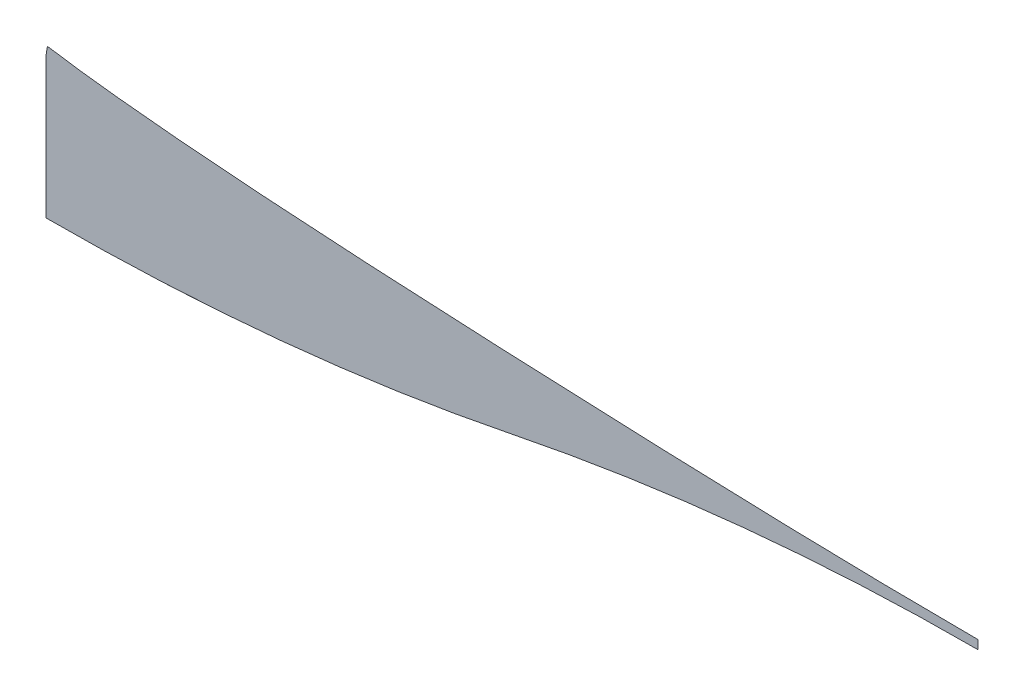
SolidWorks part; units mm, degrees
ref_plane "Front Plane" through (0, 0, 0) normal (0, 0, 1) x (1, 0, 0)
ref_plane "Top Plane" through (0, 0, 0) normal (0, 1, 0) x (1, 0, 0)
ref_plane "Right Plane" through (0, 0, 0) normal (1, 0, 0) x (0, 0, -1)
sketch "Sketch1" plane through (0, 0, 0) normal (0, 0, 1) x (1, 0, 0)
  line L0 (-2512.0431, -12.6587) -> (-2512.0431, -412.6587)
  line L1 (-2512.0431, -412.6587) -> (-3597.8043, -412.6587)
  line L2 (-2508.0244, 12.0162) -> (-2512.0431, -12.6587)
  line L3 (975.7674, -126.4275) -> (975.7674, -101.373)
  line L4 (-2508.0244, 12.0162) -> (-2512.0431, -12.6587)
  line L5 (975.7674, -126.4275) -> (975.7674, -101.373)
  line L6 (137.9569, -150.9051) -> (137.9569, -125.905)
  arc A0 (137.9569, -150.9051) -> (-1187.0431, -282.6587) centre (127.7172, -6776.335) ccw
  spline S0 degree 3 poles (-1187.0431, -282.6587) (-1624.8299, -371.2964) (-2064.0186, -412.6587) (-2512.0431, -412.6587) knots 0 0 0 0 1 1 1 1
  spline S2 degree 3 poles (-6454.5938, 654.8266) (-2679.9259, 21.8706) (-2615.1536, 3.7256) (-2498.0428, -14.9032) (-2487.8361, -16.4895) (-2475.3324, -18.375) (-2458.3336, -20.8637) (-2436.4762, -23.9285) (-2409.3029, -27.5342) (-2381.214, -31.0693) (-2342.5806, -35.6905) (-2292.1476, -41.2975) (-2228.4421, -47.7643) (-2161.7936, -53.9783) (-2092.4467, -59.9479) (-1996.7192, -67.5927) (-1871.5631, -76.5793) (-1714.5686, -86.5176) (-1552.7616, -95.674) (-1388.1075, -104.1126) (-1250.1388, -110.5995) (-1140.2607, -115.4933) (-1058.3256, -119.0245) (-977.0535, -122.427) (-897.2422, -125.6742) (-818.7127, -128.7595) (-715.5547, -132.6501) (-589.2496, -137.0801) (-441.1109, -141.6494) (-295.695, -145.4108) (-152.3566, -148.2965) (-10.4989, -150.2182) (130.4752, -151.0881) (271.1761, -150.7798) (412.21, -149.1666) (554.2654, -146.0765) (698.1098, -141.2998) (820.2292, -135.6915) (1749.8876, -83.0796) (2865.1169, 98.3937) (4867.2241, 755.6905) knots 0.150231 0.150231 0.150231 0.150231 0.257796 0.259745 0.263642 0.267539 0.271436 0.279231 0.287025 0.294819 0.302614 0.318203 0.333791 0.34938 0.364969 0.380557 0.411735 0.442912 0.47409 0.505267 0.536445 0.552033 0.567622 0.583211 0.5988 0.614388 0.629977 0.661154 0.692332 0.723509 0.754687 0.785864 0.817042 0.848219 0.879397 0.910574 0.941751 0.972929 0.988518 1.523779 1.523779 1.523779 1.523779 only from (-2512.0431, -12.6587) to (975.7674, -126.4275)
  spline S3 degree 3 poles (4887.5404, 702.9336) (2680.6744, 87.552) (1616.7887, -73.49) (704.536, -116.0261) (560.5486, -120.8946) (418.37, -124.0613) (230.1742, -126.2974) (-4.2222, -125.8049) (-241.5717, -121.7799) (-435.6236, -116.7956) (-583.8946, -112.2437) (-735.6055, -106.9397) (-865.5648, -101.9378) (-958.7687, -98.1518) (-1012.7749, -95.9095) (-1094.326, -92.4747) (-1217.9524, -87.0792) (-1383.8076, -79.2935) (-1548.7608, -70.8533) (-1764.8871, -58.6426) (-1971.3229, -44.8694) (-3178.2725, 54.8392) (-3277.35, 236.5319) (1427.353, 604.618) knots -0.492362 -0.492362 -0.492362 -0.492362 0.028062 0.059312 0.090562 0.121812 0.153062 0.215562 0.278062 0.309312 0.340562 0.371812 0.403062 0.418687 0.4265 0.434312 0.465562 0.496812 0.528062 0.559312 0.621812 0.653062 1.35898 1.35898 1.35898 1.35898 only from (975.7674, -101.373) to (-2508.0244, 12.0162)
  spline S4 degree 3 poles (-2512.0431, -12.6587) (-2510.0545, -12.9826) (-2506.0914, -13.6229) (-2498.0428, -14.9032) (-2487.8361, -16.4895) (-2475.3324, -18.375) (-2458.3336, -20.8637) (-2436.4762, -23.9285) (-2409.3029, -27.5342) (-2381.214, -31.0693) (-2342.5806, -35.6905) (-2292.1476, -41.2975) (-2228.4421, -47.7643) (-2161.7936, -53.9783) (-2092.4467, -59.9479) (-1996.7192, -67.5927) (-1871.5631, -76.5793) (-1714.5686, -86.5176) (-1552.7616, -95.674) (-1388.1075, -104.1126) (-1250.1388, -110.5995) (-1140.2607, -115.4933) (-1058.3256, -119.0245) (-977.0535, -122.427) (-897.2422, -125.6742) (-818.7127, -128.7595) (-715.5547, -132.6501) (-589.2496, -137.0801) (-441.1109, -141.6494) (-295.695, -145.4108) (-152.3566, -148.2965) (-10.4989, -150.2182) (130.4752, -151.0881) (271.1761, -150.7798) (412.21, -149.1666) (554.2654, -146.0765) (698.1098, -141.2998) (820.2292, -135.6915) (913.2681, -130.4261) (957.0766, -127.661) (975.7674, -126.4275) knots 0.255848 0.255848 0.255848 0.255848 0.257796 0.259745 0.263642 0.267539 0.271436 0.279231 0.287025 0.294819 0.302614 0.318203 0.333791 0.34938 0.364969 0.380557 0.411735 0.442912 0.47409 0.505267 0.536445 0.552033 0.567622 0.583211 0.5988 0.614388 0.629977 0.661154 0.692332 0.723509 0.754687 0.785864 0.817042 0.848219 0.879397 0.910574 0.941751 0.972929 0.988518 1 1 1 1
  spline S5 degree 3 poles (975.7674, -101.373) (933.9571, -104.1395) (842.6289, -109.5872) (704.536, -116.0261) (560.5486, -120.8946) (418.37, -124.0613) (230.1742, -126.2974) (-4.2222, -125.8049) (-241.5717, -121.7799) (-435.6236, -116.7956) (-583.8946, -112.2437) (-735.6055, -106.9397) (-865.5648, -101.9378) (-958.7687, -98.1518) (-1012.7749, -95.9095) (-1094.326, -92.4747) (-1217.9524, -87.0792) (-1383.8076, -79.2935) (-1548.7608, -70.8533) (-1764.8871, -58.6426) (-1971.3229, -44.8694) (-2254.3194, -21.4905) (-2413.8411, -3.3232) (-2508.0244, 12.0162) knots 0.002322 0.002322 0.002322 0.002322 0.028062 0.059312 0.090562 0.121812 0.153062 0.215562 0.278062 0.309312 0.340562 0.371812 0.403062 0.418687 0.4265 0.434312 0.465562 0.496812 0.528062 0.559312 0.621812 0.653062 0.746812 0.746812 0.746812 0.746812
  dimension "D2" = 2650
  dimension "D3" = 1325
  dimension "D4" = 270
  dimension "D5" = 400
  dimension "D1" = 0
extrude "Boss-Extrude1" add sketch "Sketch1" along normal blind 0.0002 contours S4 L0 S0 A0 | L6 S5 L4 S4
